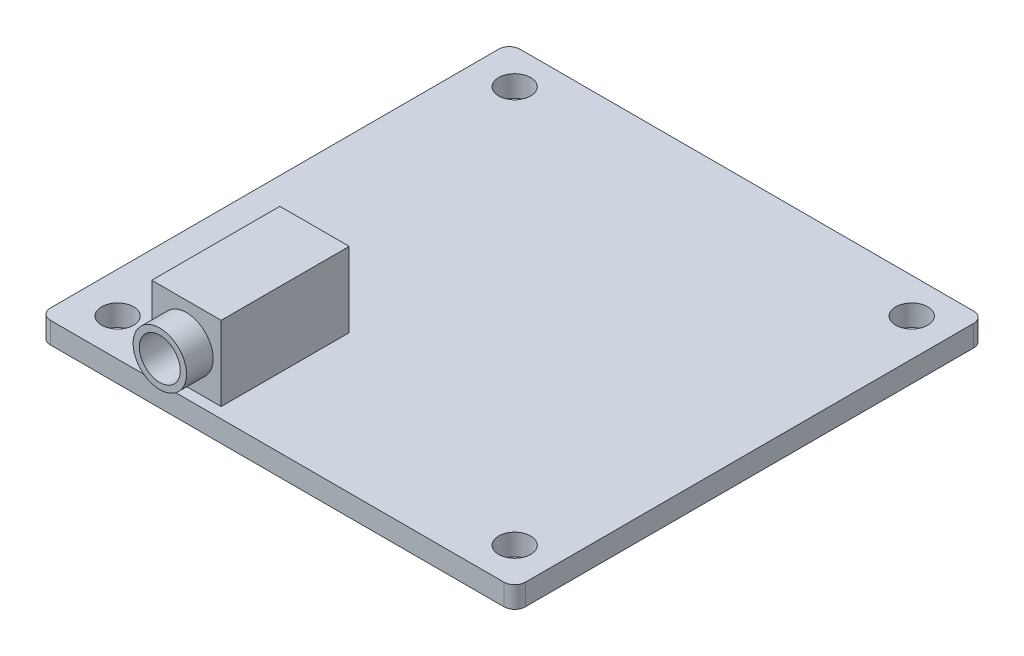
SolidWorks part; units mm, degrees
ref_plane "Front Plane" through (0, 0, 0) normal (0, 0, 1) x (1, 0, 0)
ref_plane "Top Plane" through (0, 0, 0) normal (0, 1, 0) x (1, 0, 0)
ref_plane "Right Plane" through (0, 0, 0) normal (1, 0, 0) x (0, 0, -1)
sketch "Sketch1" plane through (0, 0, 0) normal (0, 1, 0) x (1, 0, 0)
  line L1 (0, 0) -> (44.5, 0)
  line L2 (0, 0) -> (0, 44)
  line L3 (0, 44) -> (44.5, 44)
  line L4 (44.5, 0) -> (44.5, 44)
  dimension "D1" = 44.5
  dimension "D2" = 44
extrude "Boss-Extrude1" add sketch "Sketch1" along normal blind 2
sketch "Sketch2" plane through (0, 2, 0) normal (0, 1, 0) x (1, 0, 0)
  line L2 (44.5, 0) -> (44.5, 44) construction
  line L3 (3.8, 40.7) -> (41, 40.7) construction
  line L4 (3.8, 40.7) -> (3.8, 3.5) construction
  line L5 (3.8, 3.5) -> (41, 3.5) construction
  line L6 (41, 40.7) -> (41, 3.5) construction
  line L7 (0, 0) -> (44.5, 0) construction
  circle A0 centre (3.8, 40.7) radius 1.5
  circle A1 centre (3.8, 3.5) radius 1.5
  circle A2 centre (41, 3.5) radius 1.5
  circle A3 centre (41, 40.7) radius 1.5
  dimension "D1" = 3
  dimension "D2" = 37.2
  dimension "D3" = 37.2
  dimension "D4" = 3.5
  dimension "D5" = 3.5
extrude "Cut-Extrude1" cut sketch "Sketch2" against normal through all
sketch "Sketch3" plane through (0, 2, 0) normal (0, 1, 0) x (1, 0, 0)
  line L0 (0, 0) -> (44.5, 0) construction
  line L1 (9.5, 13) -> (16, 13)
  line L2 (9.5, 13) -> (9.5, 1)
  line L3 (9.5, 1) -> (16, 1)
  line L4 (16, 13) -> (16, 1)
  line L5 (0, 44) -> (0, 0) construction
  dimension "D1" = 6.5
  dimension "D2" = 12
  dimension "D3" = 1
  dimension "D4" = 16
extrude "Boss-Extrude2" add sketch "Sketch3" along normal blind 7
sketch "Sketch4" plane through (0, 0, -1) normal (0, 0, 1) x (1, 0, 0)
  line L0 (16, 9) -> (16, 2) construction
  line L1 (9.5, 9) -> (16, 9) construction
  circle A0 centre (12.75, 5.5) radius 2.5
  dimension "D1" = 5
  dimension "D2" = 3.25
  dimension "D3" = 3.5
extrude "Boss-Extrude3" add sketch "Sketch4" along normal blind 2.5
sketch "Sketch5" plane through (0, 0, 1.5) normal (0, 0, 1) x (1, 0, 0)
  circle A0 centre (12.75, 5.5) radius 1.921
extrude "Cut-Extrude2" cut sketch "Sketch5" against normal blind 11.5
fillet "Fillet1" radius 1 4 edges at (0, 1, 0) (44.5, 1, 0) (44.5, 1, -44) (0, 1, -44)
